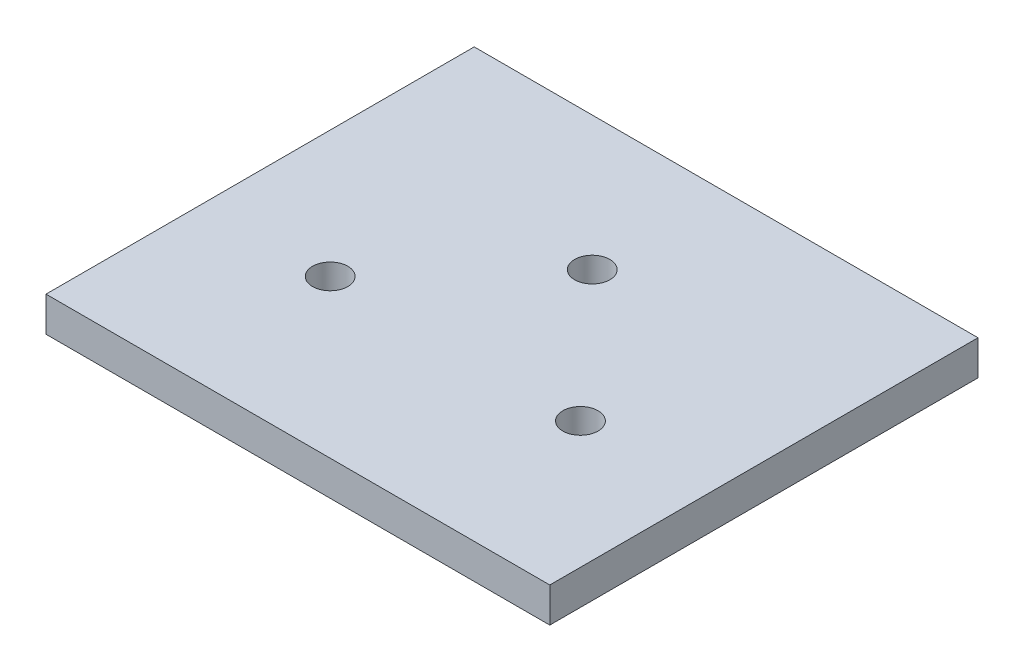
SolidWorks part; units mm, degrees
ref_plane "Front Plane" through (0, 0, 0) normal (0, 0, 1) x (1, 0, 0)
ref_plane "Top Plane" through (0, 0, 0) normal (0, 1, 0) x (1, 0, 0)
ref_plane "Right Plane" through (0, 0, 0) normal (1, 0, 0) x (0, 0, -1)
sketch "Sketch1" plane through (0, 0, 0) normal (0, 1, 0) x (1, 0, 0)
  line L0 (0, 0) -> (0, 31.25) construction
  line L5 (0, 80.9292) -> (0, 31.25) construction
  line L6 (50, 0) -> (-50, 0)
  line L7 (-24.8396, 31.25) -> (24.8396, 31.25) construction
  line L8 (-50, 0) -> (-50, 85)
  line L9 (-50, 85) -> (50, 85)
  line L10 (50, 0) -> (50, 85)
  circle A0 centre (-24.8396, 31.25) radius 36.82 construction
  circle A2 centre (0, 58.4292) radius 36.82 construction
  circle A3 centre (24.8396, 31.25) radius 36.82 construction
  circle A4 centre (0, 58.4292) radius 22.5 construction
  circle A5 centre (24.8396, 31.25) radius 22.5 construction
  circle A6 centre (-24.8396, 31.25) radius 22.5 construction
  circle A7 centre (0, 58.4292) radius 3.5
  circle A8 centre (24.8396, 31.25) radius 3.5
  circle A9 centre (-24.8396, 31.25) radius 3.5
  point P0 (0, 0)
  point P17 (0, 85)
  point P22 (0, 85)
  dimension "D5" = 7
  dimension "D6" = 7
  dimension "D3" = 73.64
  dimension "D2" = 45
  dimension "D4" = 7
  dimension "D1" = 31.25
  dimension "D7" = 100
  dimension "D8" = 85
extrude "Boss-Extrude1" add sketch "Sketch1" along normal blind 6.9
